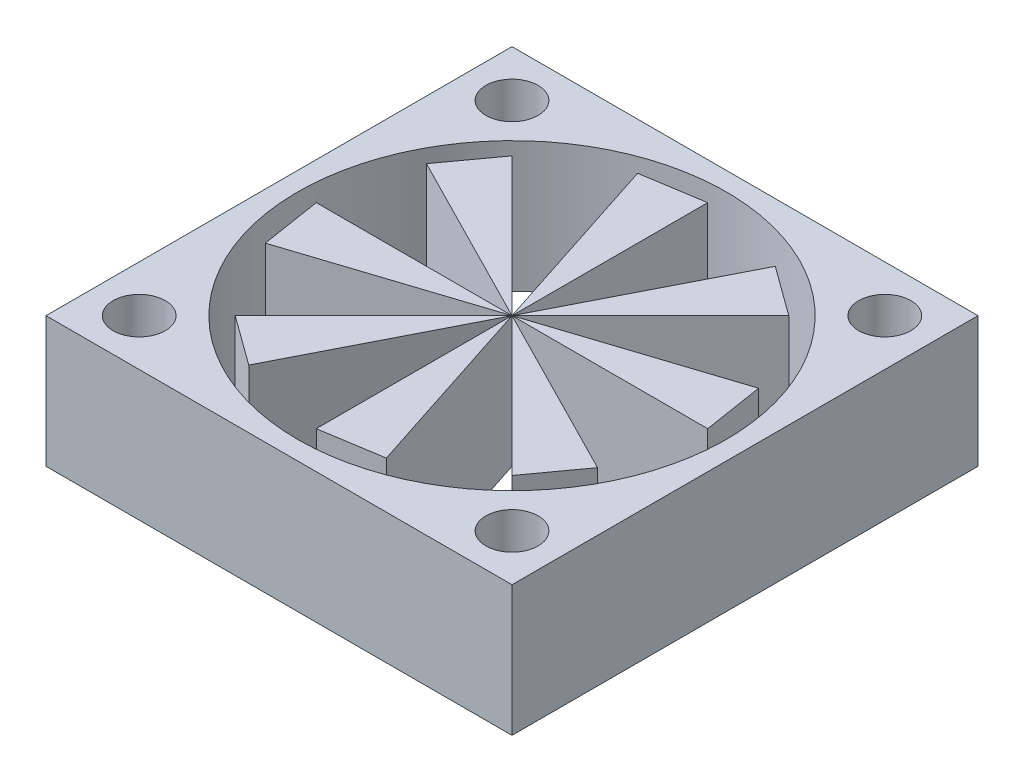
SolidWorks part; units mm, degrees
ref_plane "前视基准面" through (0, 0, 0) normal (0, 0, 1) x (1, 0, 0)
ref_plane "上视基准面" through (0, 0, 0) normal (0, 1, 0) x (1, 0, 0)
ref_plane "右视基准面" through (0, 0, 0) normal (1, 0, 0) x (0, 0, -1)
sketch "草图1" plane through (0, 0, 0) normal (0, 1, 0) x (1, 0, 0)
  line L0 (0, 12.5) -> (0, -12.5) construction
  line L1 (-12.5, 12.5) -> (12.5, 12.5)
  line L2 (-12.5, 12.5) -> (-12.5, -12.5)
  line L3 (-12.5, -12.5) -> (12.5, -12.5)
  line L4 (12.5, 12.5) -> (12.5, -12.5)
  line L5 (-12.5, 0) -> (12.5, 0) construction
  circle A0 centre (-10, 10) radius 1.4
  circle A4 centre (0, 0) radius 11.5
  circle A5 centre (10, 10) radius 1.4
  circle A6 centre (10, -10) radius 1.4
  circle A7 centre (-10, -10) radius 1.4
  point P10 (0, 0)
  dimension "D6" = 2.8
  dimension "D7" = 23
  dimension "D1" = 25
  dimension "D2" = 25
  dimension "D3" = 10
  dimension "D4" = 10
  dimension "D5" = 4
extrude "凸台-拉伸1" add sketch "草图1" along normal blind 7
sketch "草图2" plane through (0, 0, 0) normal (0, -1, 0) x (1, 0, 0)
  line L0 (12.5, -12.5) -> (-12.5, -12.5) construction
  line L1 (0, -12.5) -> (0, 12.5) construction
  line L2 (-12.5, 12.5) -> (12.5, 12.5) construction
  line L3 (12.5, 0) -> (-12.5, 0) construction
  line L4 (12.5, 12.5) -> (12.5, -12.5) construction
  line L5 (-12.5, -12.5) -> (-12.5, 12.5) construction
  line L6 (0, 0) -> (0, -10.5)
  line L7 (0, -10.5) -> (-3.2447, -9.9861)
  line L8 (-3.2447, -9.9861) -> (0, 0)
  line L9 (-7.4246, -7.4246) -> (-9.3556, -4.7669)
  line L10 (-9.3556, -4.7669) -> (0, 0)
  line L11 (0, 0) -> (-7.4246, -7.4246)
  line L12 (-10.5, 0) -> (-9.9861, 3.2447)
  line L13 (-9.9861, 3.2447) -> (0, 0)
  line L14 (0, 0) -> (-10.5, 0)
  line L15 (-7.4246, 7.4246) -> (-4.7669, 9.3556)
  line L16 (-4.7669, 9.3556) -> (0, 0)
  line L17 (0, 0) -> (-7.4246, 7.4246)
  line L18 (0, 10.5) -> (3.2447, 9.9861)
  line L19 (3.2447, 9.9861) -> (0, 0)
  line L20 (0, 0) -> (0, 10.5)
  line L21 (7.4246, 7.4246) -> (9.3556, 4.7669)
  line L22 (9.3556, 4.7669) -> (0, 0)
  line L23 (0, 0) -> (7.4246, 7.4246)
  line L24 (10.5, 0) -> (9.9861, -3.2447)
  line L25 (9.9861, -3.2447) -> (0, 0)
  line L26 (0, 0) -> (10.5, 0)
  line L27 (7.4246, -7.4246) -> (4.7669, -9.3556)
  line L28 (4.7669, -9.3556) -> (0, 0)
  line L29 (0, 0) -> (7.4246, -7.4246)
  dimension "D1" = 10.5
  dimension "D2" = 10.5
  dimension "D3" = 18
  dimension "D4" = 8
extrude "凸台-拉伸2" add sketch "草图2" against normal blind 7 separate body contours L29 L28 L27 | L8 L7 L6 | L11 L10 L9 | L14 L13 L12 | L17 L16 L15 | L20 L19 L18 | L23 L22 L21 | L26 L25 L24
